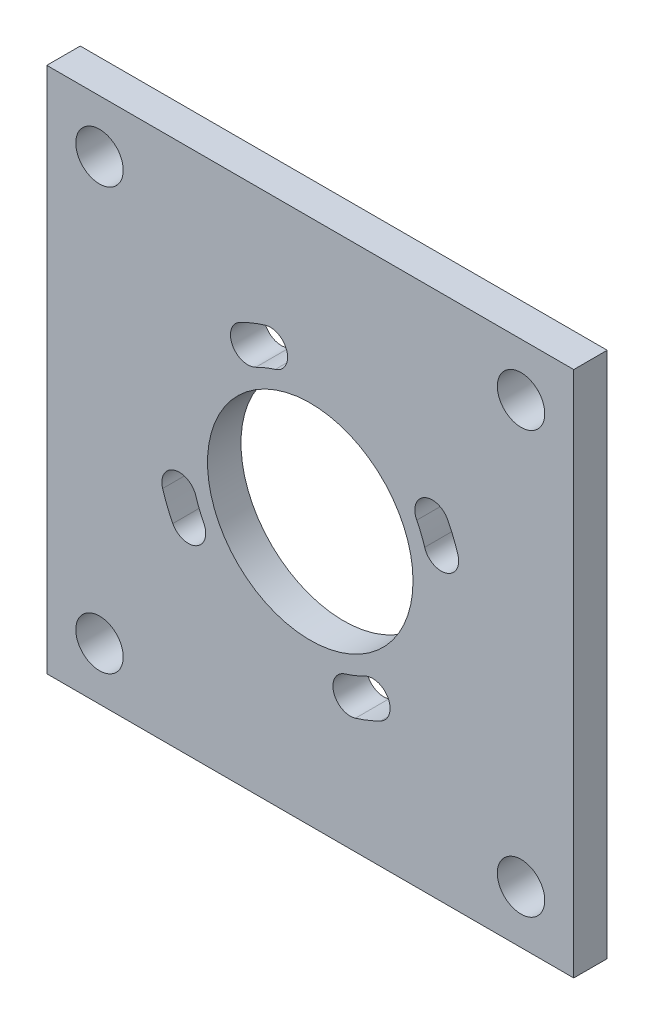
SolidWorks part; units mm, degrees
material "6061-T6 (SS)"
ref_plane "Front Plane" through (0, 0, 0) normal (0, 0, 1) x (1, 0, 0)
ref_plane "Top Plane" through (0, 0, 0) normal (0, 1, 0) x (1, 0, 0)
ref_plane "Right Plane" through (0, 0, 0) normal (1, 0, 0) x (0, 0, -1)
sketch "Sketch1" plane through (0, 0, 0) normal (0, 0, 1) x (1, 0, 0)
  line L1 (-25, 25) -> (25, 25)
  line L2 (-25, 25) -> (-25, -25)
  line L3 (-25, -25) -> (25, -25)
  line L4 (25, 25) -> (25, -25)
  line L5 (-25, 25) -> (25, -25) construction
  line L6 (-25, -25) -> (25, 25) construction
  point P0 (0, 0)
  dimension "D1" = 50
  dimension "D2" = 50
extrude "Boss-Extrude1" add sketch "Sketch1" along normal blind 3.175
sketch "Sketch2" plane through (0, 0, 3.175) normal (0, 0, 1) x (1, 0, 0)
  circle A0 centre (0, 0) radius 9.75
  dimension "D1" = 19.5
extrude "Cut-Extrude1" cut sketch "Sketch2" against normal through all
sketch "Sketch3" plane through (0, 0, 3.175) normal (0, 0, 1) x (1, 0, 0)
  line L0 (0, 0) -> (0, 25) construction
  line L1 (8.4168, 25) -> (8.4168, 13) construction
  line L2 (8.4168, 13) -> (7.5473, 29.5921) construction
  line L3 (25, 25) -> (-25, 25) construction
  line L4 (0, 0) -> (-5.924, 11.5718) construction
  line L6 (-205.3627, 853.9557) -> (706.6373, 853.9557) construction
  line L7 (-3.8008, 12.432) -> (0, 0) construction
  circle A5 centre (0, 0) radius 13 construction
  arc A10 (-3.8008, 12.432) -> (-5.924, 11.5718) centre (0, 0) ccw construction
  arc A11 (-4.2832, 14.0099) -> (-6.6758, 13.0405) centre (0, 0) ccw
  arc A12 (-3.3184, 10.8541) -> (-5.1721, 10.1031) centre (0, 0) ccw
  arc A13 (-3.3184, 10.8541) -> (-4.2832, 14.0099) centre (-3.8008, 12.432) ccw
  arc A14 (-6.6758, 13.0405) -> (-5.1721, 10.1031) centre (-5.924, 11.5718) ccw
  arc A15 (12.432, 3.8008) -> (11.5718, 5.924) centre (0, 0) ccw construction
  arc A16 (14.0099, 4.2832) -> (13.0405, 6.6758) centre (0, 0) ccw
  arc A17 (10.8541, 3.3184) -> (10.1031, 5.1721) centre (0, 0) ccw
  arc A18 (10.8541, 3.3184) -> (14.0099, 4.2832) centre (12.432, 3.8008) ccw
  arc A19 (13.0405, 6.6758) -> (10.1031, 5.1721) centre (11.5718, 5.924) ccw
  arc A20 (3.8008, -12.432) -> (5.924, -11.5718) centre (0, 0) ccw construction
  arc A21 (4.2832, -14.0099) -> (6.6758, -13.0405) centre (0, 0) ccw
  arc A22 (3.3184, -10.8541) -> (5.1721, -10.1031) centre (0, 0) ccw
  arc A23 (3.3184, -10.8541) -> (4.2832, -14.0099) centre (3.8008, -12.432) ccw
  arc A24 (6.6758, -13.0405) -> (5.1721, -10.1031) centre (5.924, -11.5718) ccw
  arc A25 (-12.432, -3.8008) -> (-11.5718, -5.924) centre (0, 0) ccw construction
  arc A26 (-14.0099, -4.2832) -> (-13.0405, -6.6758) centre (0, 0) ccw
  arc A27 (-10.8541, -3.3184) -> (-10.1031, -5.1721) centre (0, 0) ccw
  arc A28 (-10.8541, -3.3184) -> (-14.0099, -4.2832) centre (-12.432, -3.8008) ccw
  arc A29 (-13.0405, -6.6758) -> (-10.1031, -5.1721) centre (-11.5718, -5.924) ccw
  point P9 (-4.8814, 12.0487)
  point P12 (-13, 0)
  point P13 (13, 0)
  point P14 (0, 13)
  point P15 (0, -13)
  point P18 (12.0487, 4.8814)
  point P29 (4.8814, -12.0487)
  point P36 (-12.0487, -4.8814)
  point P42 (0, 0)
  dimension "D5" = 3.3
  dimension "D6" = 2
  dimension "D7" = 12
  dimension "D8" = 10.109
  dimension "D1" = 26
  dimension "D2" = 4
  dimension "D3" = 3
  dimension "D4" = 17
extrude "Cut-Extrude2" cut sketch "Sketch3" against normal through all
sketch "Sketch4" plane through (0, 0, 3.175) normal (0, 0, 1) x (1, 0, 0)
  line L0 (-25, 25) -> (25, -25) construction
  line L1 (25, 25) -> (-25, -25) construction
  line L2 (0, 0) -> (-42.2173, 0) construction
  line L3 (0, 25) -> (0, 0) construction
  line L4 (25, 25) -> (-25, 25) construction
  circle A0 centre (-20, 20) radius 2.25
  circle A4 centre (-20, -20) radius 2.25
  circle A5 centre (20, 20) radius 2.25
  circle A6 centre (20, -20) radius 2.25
  point P8 (-20, 20)
  dimension "D7" = 4.5
  dimension "D4" = 20
extrude "Cut-Extrude3" cut sketch "Sketch4" against normal through all
